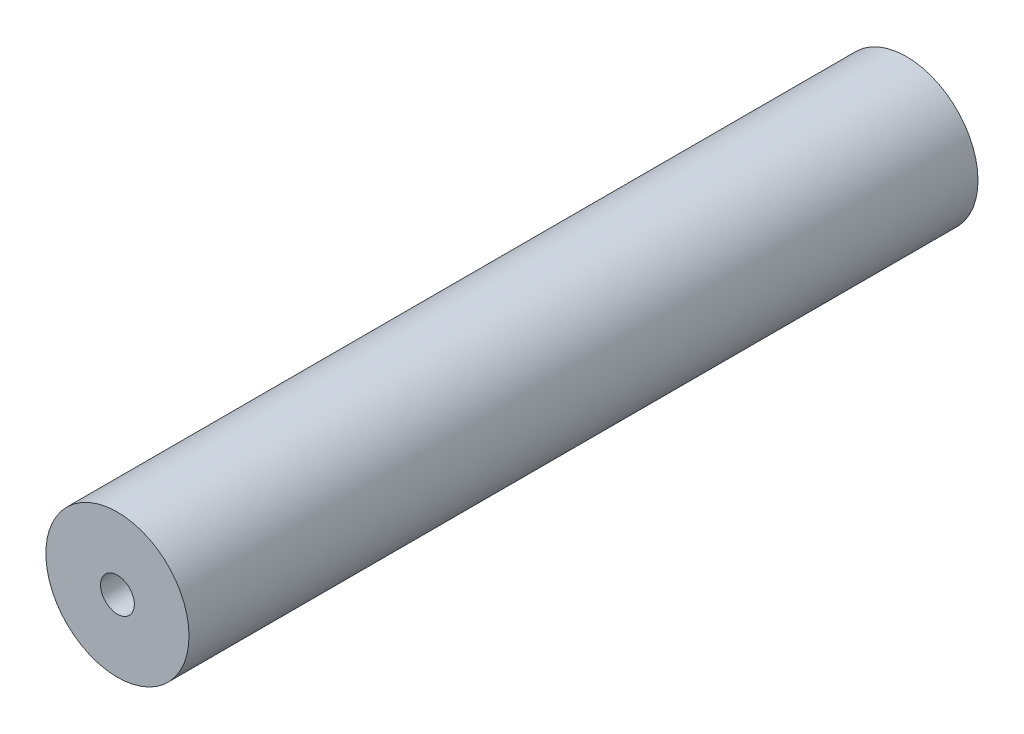
SolidWorks part; units mm, degrees
ref_plane "Front Plane" through (0, 0, 0) normal (0, 0, 1) x (1, 0, 0)
ref_plane "Top Plane" through (0, 0, 0) normal (0, 1, 0) x (1, 0, 0)
ref_plane "Right Plane" through (0, 0, 0) normal (1, 0, 0) x (0, 0, -1)
sketch "Croquis1" plane through (0, 0, 0) normal (0, 0, 1) x (1, 0, 0)
  circle A0 centre (0, 0) radius 6.35
extrude "Saliente-Extruir1" add sketch "Croquis1" along normal blind 70
sketch "Croquis2" plane through (0, 0, 70) normal (0, 0, 1) x (1, 0, 0)
  circle A0 centre (0, 0) radius 1.5
extrude "Cortar-Extruir1" cut sketch "Croquis2" against normal blind 20
sketch "Croquis3" plane through (0, 0, 0) normal (0, 0, -1) x (-1, 0, 0)
  circle A0 centre (0, 0) radius 1.5
extrude "Cortar-Extruir2" cut sketch "Croquis3" against normal blind 20
